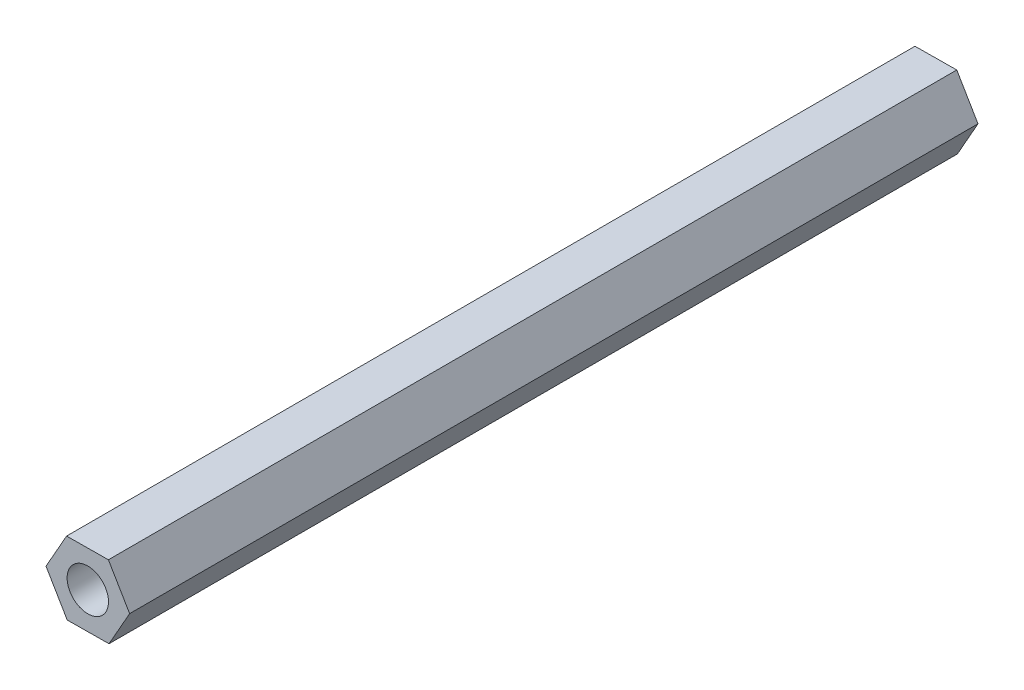
SolidWorks part; units mm, degrees
ref_plane "前视基准面" through (0, 0, 0) normal (0, 0, 1) x (1, 0, 0)
ref_plane "上视基准面" through (0, 0, 0) normal (0, 1, 0) x (1, 0, 0)
ref_plane "右视基准面" through (0, 0, 0) normal (1, 0, 0) x (0, 0, -1)
sketch "草图1" plane through (0, 0, 0) normal (0, 0, 1) x (1, 0, 0)
  line L1 (2.0515, -3.4821) -> (4.0413, 0.0356)
  line L2 (4.0413, 0.0356) -> (1.9898, 3.5177)
  line L3 (1.9898, 3.5177) -> (-2.0515, 3.4821)
  line L4 (-2.0515, 3.4821) -> (-4.0413, -0.0356)
  line L5 (-4.0413, -0.0356) -> (-1.9898, -3.5177)
  line L6 (-1.9898, -3.5177) -> (2.0515, -3.4821)
  circle A0 centre (0, 0) radius 3.5 construction
  circle A1 centre (0, 0) radius 2
extrude "凸台-拉伸1" add sketch "草图1" along normal blind 82
